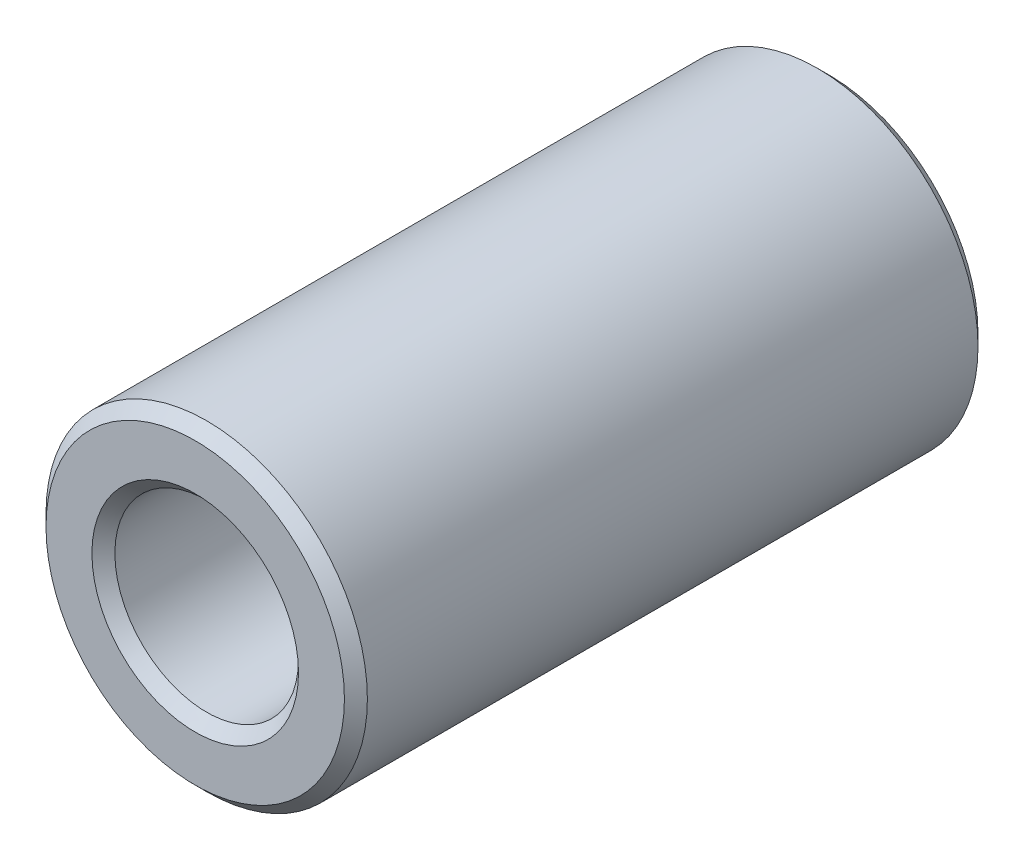
SolidWorks part; units mm, degrees
ref_plane "Plan1" through (0, 0, 0) normal (0, 0, 1) x (1, 0, 0)
ref_plane "Plan2" through (0, 0, 0) normal (0, 1, 0) x (1, 0, 0)
ref_plane "Plan3" through (0, 0, 0) normal (1, 0, 0) x (0, 0, -1)
sketch "Esquisse1" plane through (0, 0, 0) normal (0, 0, 1) x (1, 0, 0)
  circle A0 centre (0, 0) radius 7
  circle A1 centre (0, 0) radius 4
  dimension "D1" = 14
  dimension "D2" = 8
extrude "Base-Extrusion" add sketch "Esquisse1" along normal blind 27.6
chamfer "Chanfrein2" distance 0.5 angle 45
